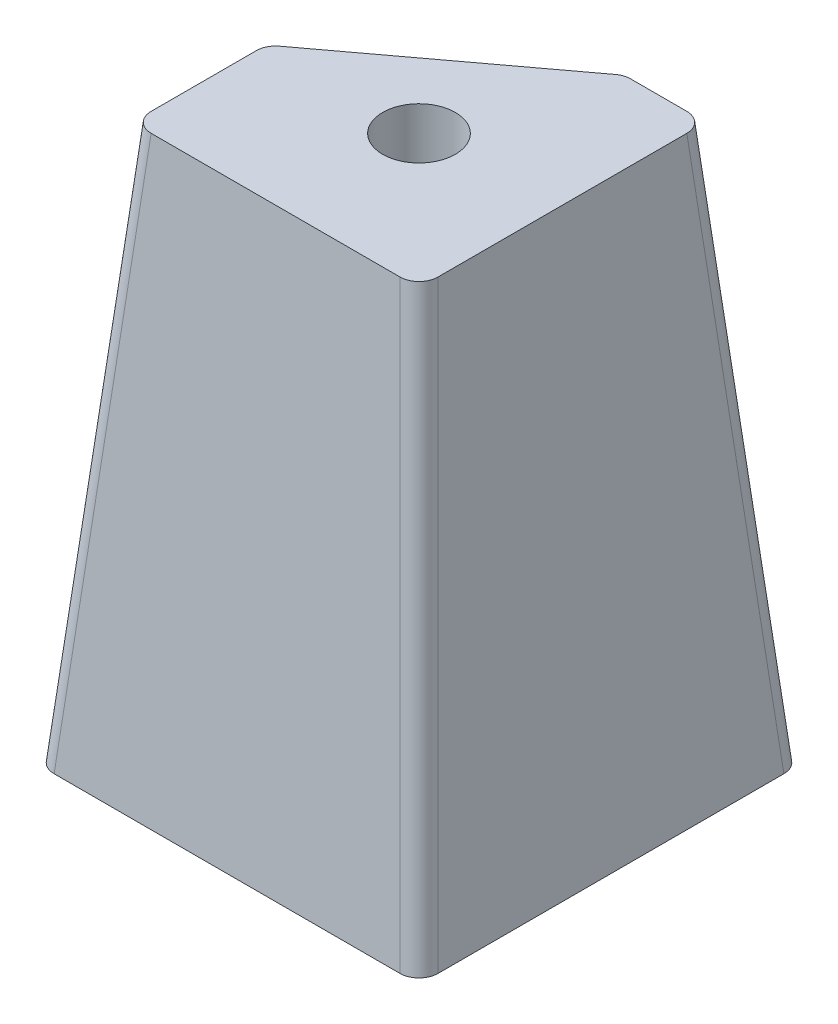
SolidWorks part; units mm, degrees
ref_plane "Front Plane" through (0, 0, 0) normal (0, 0, 1) x (1, 0, 0)
ref_plane "Top Plane" through (0, 0, 0) normal (0, 1, 0) x (1, 0, 0)
ref_plane "Right Plane" through (0, 0, 0) normal (1, 0, 0) x (0, 0, -1)
sketch "Sketch1" plane through (0, 0, 0) normal (0, 1, 0) x (1, 0, 0)
  line L0 (-4.5796, -0.2013) -> (6.1532, 7.7987)
  line L1 (6.1532, 7.7987) -> (10.4204, 7.7987)
  line L2 (10.4204, 7.7987) -> (10.4204, -7.2013)
  line L3 (10.4204, -7.2013) -> (-4.5796, -7.2013)
  line L4 (-4.5796, -7.2013) -> (-4.5796, -0.2013)
  dimension "D1" = 15
  dimension "D2" = 15
  dimension "D4" = 7
  dimension "D5" = 126.7
extrude "Boss-Extrude1" add sketch "Sketch1" along normal blind 29
sketch "Sketch2" plane through (0, 0, 0) normal (0, -1, 0) x (1, 0, 0)
  line L0 (-4.5796, 0.2013) -> (-4.5796, 7.2013) construction
  line L1 (10.4204, 7.2013) -> (10.4204, -7.7987) construction
  line L2 (-4.5796, 7.2013) -> (10.4204, 7.2013) construction
  circle A0 centre (-0.5796, 2.2013) radius 1.5
  circle A1 centre (7.4204, 2.2013) radius 2
  dimension "D1" = 3
  dimension "D3" = 4
  dimension "D2" = 4
  dimension "D4" = 3
  dimension "D5" = 5
  dimension "D6" = 5
extrude "Cut-Extrude1" cut sketch "Sketch2" against normal blind 10
sketch "Sketch3" plane through (0, 29, 0) normal (0, 1, 0) x (1, 0, 0)
  line L0 (10.4204, -7.2013) -> (10.4204, 7.7987) construction
  line L1 (-4.5796, -7.2013) -> (10.4204, -7.2013) construction
  circle A0 centre (3.4204, -0.2013) radius 1.9
  dimension "D1" = 3.8
  dimension "D2" = 7
  dimension "D3" = 7
extrude "Cut-Extrude2" cut sketch "Sketch3" against normal blind 6
draft "Draft1" type of draft neutral plane draft angle 5 faces to draft 5 face at (8.2868, 14.5, -7.7987) face at (10.4204, 14.5, -0.2987) face at (2.9204, 14.5, 7.2013) face at (-4.5796, 14.5, 3.7013) face at (0.7868, 14.5, -3.7987) neutral plane through (0, 29, 0) neutral plane normal (0, 1, 0) parameters "D1"=5
fillet "Fillet1" radius 1 5 edges at (5.7324, 14.5, -9.0673) (-5.8482, 14.5, -0.4353) (11.6889, 14.5, -9.0673) (11.6889, 14.5, 8.4699) (-5.8482, 14.5, 8.4699)
